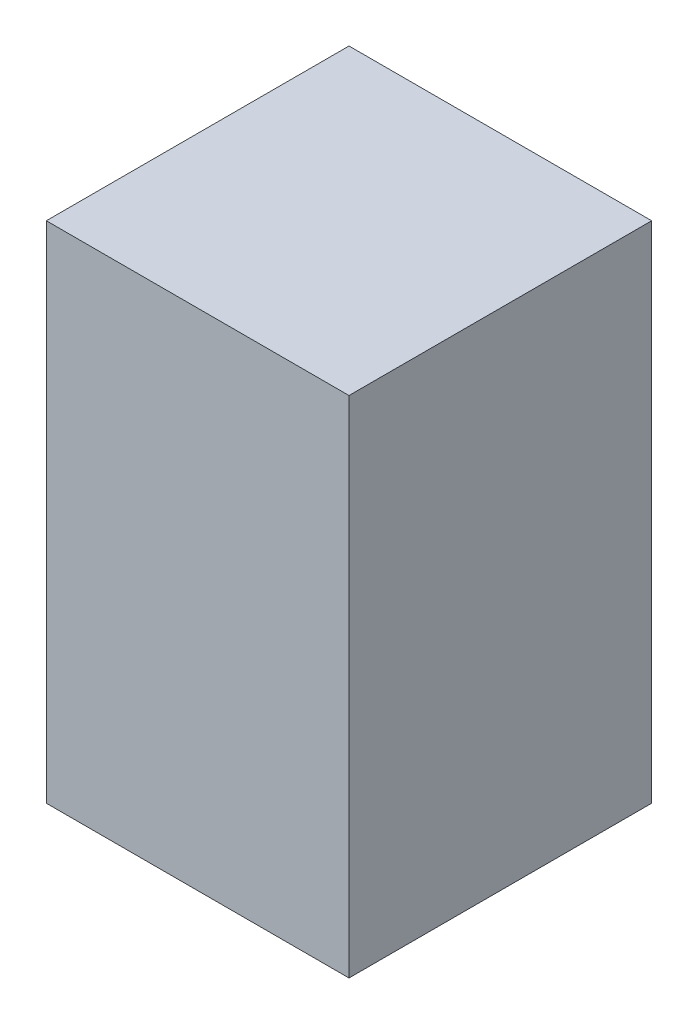
SolidWorks part; units mm, degrees
material "Balsa"
ref_plane "Front Plane" through (0, 0, 0) normal (0, 0, 1) x (1, 0, 0)
ref_plane "Top Plane" through (0, 0, 0) normal (0, 1, 0) x (1, 0, 0)
ref_plane "Right Plane" through (0, 0, 0) normal (1, 0, 0) x (0, 0, -1)
sketch "Sketch1" plane through (0, 0, 0) normal (0, 1, 0) x (1, 0, 0)
  line L1 (-15, -15) -> (15, -15)
  line L2 (-15, -15) -> (-15, 15)
  line L3 (-15, 15) -> (15, 15)
  line L4 (15, -15) -> (15, 15)
  line L5 (-15, -15) -> (15, 15) construction
  line L6 (-15, 15) -> (15, -15) construction
  point P0 (0, 0)
  dimension "D1" = 30
  dimension "D2" = 30
extrude "Boss-Extrude1" add sketch "Sketch1" along normal blind 50
sketch "Sketch2" plane through (0, 50, 0) normal (0, 1, 0) x (1, 0, 0)
  circle A0 centre (0, 0) radius 5 construction
  dimension "D1" = 10
